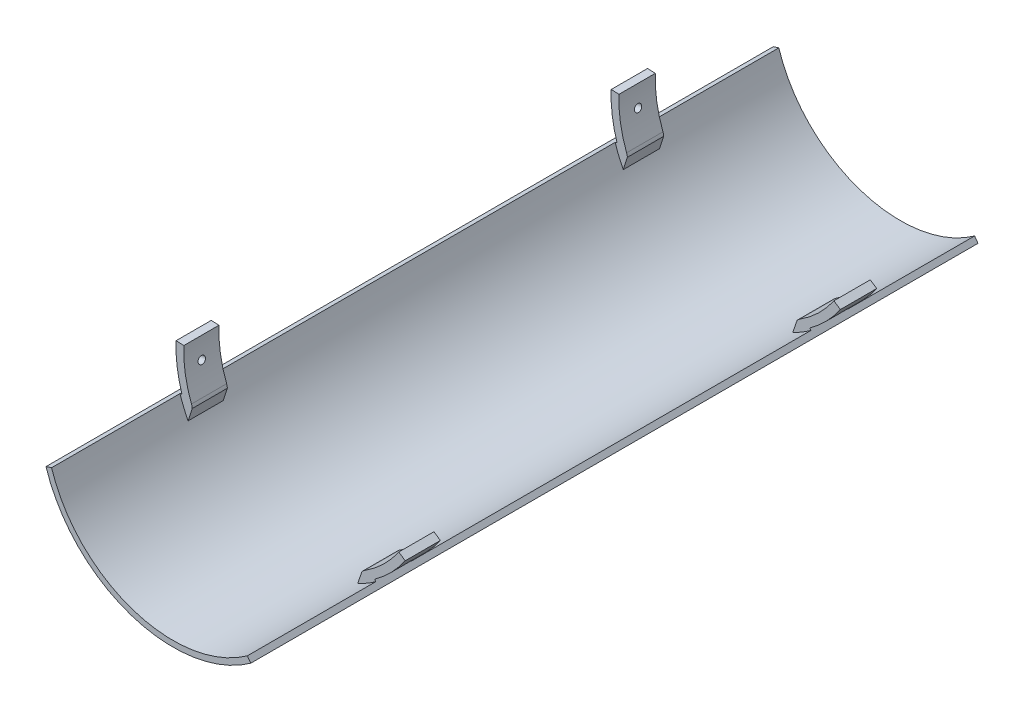
SolidWorks part; units mm, degrees
ref_plane "前视基准面" through (0, 0, 0) normal (0, 0, 1) x (1, 0, 0)
ref_plane "上视基准面" through (0, 0, 0) normal (0, 1, 0) x (1, 0, 0)
ref_plane "右视基准面" through (0, 0, 0) normal (1, 0, 0) x (0, 0, -1)
other "Configuration Table"
sketch "草图1" plane through (0, 0, 0) normal (0, 0, 1) x (1, 0, 0)
  line L0 (0, 0) -> (-52.4132, -16.6691) construction
  line L1 (0, 0) -> (32.0498, -44.6969) construction
  line L2 (-52.4132, -16.6691) -> (-49.3637, -15.6993)
  line L3 (30.1851, -42.0963) -> (32.0498, -44.6969)
  arc A0 (-49.3637, -15.6993) -> (30.1851, -42.0963) centre (0, 0) ccw
  arc A1 (-52.4132, -16.6691) -> (32.0498, -44.6969) centre (0, 0) ccw
  dimension "D1" = 110
  dimension "D2" = 103.6
  dimension "D3" = 108
extrude "凸台-拉伸1" add sketch "草图1" along normal mid plane 300
sketch "草图2" plane through (0, 0, -150) normal (0, 0, -1) x (-1, 0, 0)
  line L0 (0, 0) -> (-30.1851, -42.0963) construction
  line L1 (0, 0) -> (17.3221, -52.201) construction
  line L2 (-24.924, -42.0029) -> (-23.5075, -46.1588)
  line L3 (-40.1208, -27.4277) -> (-42.7625, -29.2337)
  line L4 (48.5589, 1.9992) -> (51.7562, 2.1309)
  line L5 (45.0905, -18.7697) -> (46.4395, -22.948)
  line L6 (0, 0) -> (-34.7485, -33.978) construction
  arc A1 (-40.1208, -27.4277) -> (-26.0428, -41.0333) centre (0, 0) ccw
  arc A2 (-32.0498, -44.6969) -> (52.4132, -16.6691) centre (0, 0) ccw construction
  arc A3 (-24.924, -42.0029) -> (-26.0428, -41.0333) centre (-28.7221, -45.2549) ccw
  arc A4 (-42.7625, -29.2337) -> (-23.5075, -46.1588) centre (0, 0) ccw
  arc A5 (51.7562, 2.1309) -> (46.4395, -22.948) centre (0, 0) cw
  arc A6 (45.0905, -18.7697) -> (45.4076, -17.3236) centre (50.0792, -19.1059) cw
  arc A7 (48.5589, 1.9992) -> (45.4076, -17.3236) centre (0, 0) cw
  dimension "D1" = 97.2
  dimension "D4" = 5
  dimension "D5" = 10
  dimension "D6" = 51.8
  dimension "D2" = 54
  dimension "D3" = 20
extrude "凸台-拉伸2" add sketch "草图2" against normal blind 247.5
sketch "草图3" plane through (0, 0, -150) normal (0, 0, -1) x (-1, 0, 0)
  circle A0 centre (0, 0) radius 52.6
extrude "切除-拉伸1" cut sketch "草图3" against normal blind 52.5
sketch "草图4" plane through (0, 0, 0) normal (0, 0, 1) x (1, 0, 0)
  circle A0 centre (0, 0) radius 52.6
extrude "切除-拉伸2" cut sketch "草图4" along normal mid plane 165
sketch "草图5" plane through (0, 0, -150) normal (0, 0, -1) x (-1, 0, 0)
  line L0 (0, 0) -> (-32.0498, -44.6969)
  line L1 (0, 0) -> (-37.0365, -36.2152)
  line L2 (0, 0) -> (30.9591, -31.6612)
  line L3 (0, 0) -> (52.4132, -16.6691)
  line L4 (0, 0) -> (55.6923, -7.4729)
  line L5 (0, 0) -> (-5.7306, -42.7077)
  arc A0 (-42.7625, -29.2337) -> (-30.1851, -42.0963) centre (0, 0) ccw construction
  dimension "D1" = 10
  dimension "D2" = 10
ref_plane "基准面1" through (0, 0, 0) normal (0.715, -0.6991, 0) x (-0.6991, -0.715, 0)
sketch "草图6" plane through (0, 0, 0) normal (0.715, -0.6991, 0) x (-0.6991, -0.715, 0)
  line L0 (0, 150) -> (0, -164.5168) construction
  circle A0 centre (0, 90) radius 1.5
  circle A1 centre (0, -90) radius 1.5
  dimension "D1" = 3
  dimension "D2" = 3
  dimension "D3" = 60
  dimension "D4" = 240
extrude "切除-拉伸3" cut sketch "草图6" along normal blind 165
ref_plane "基准面3" through (0, 0, 0) normal (0.9911, 0.133, 0) x (0.133, -0.9911, 0)
sketch "草图7" plane through (0, 0, 0) normal (0.9911, 0.133, 0) x (0.133, -0.9911, 0)
  line L0 (0, 150) -> (0, -135.6873) construction
  circle A0 centre (0, 90) radius 1.5
  circle A1 centre (0, -90) radius 1.5
  dimension "D3" = 3
  dimension "D4" = 3
  dimension "D1" = 60
  dimension "D2" = 240
extrude "切除-拉伸4" cut sketch "草图7" against normal blind 165
sketch "草图8" plane through (0, 0, -150) normal (0, 0, -1) x (-1, 0, 0)
  line L0 (-24.924, -42.0029) -> (-23.1321, -47.2405)
  line L1 (45.0905, -18.7697) -> (46.7894, -24.0315)
  line L2 (-24.924, -42.0029) -> (45.0905, -18.7697)
  arc A0 (-23.1321, -47.2405) -> (46.7894, -24.0315) centre (0, 0) ccw
  dimension "D1" = 52.6
extrude "切除-拉伸5" cut sketch "草图8" against normal blind 500
sketch "草图9" plane through (0, 0, 150) normal (0, 0, 1) x (1, 0, 0)
  circle A0 centre (0, 0) radius 52.6
extrude "切除-拉伸6" cut sketch "草图9" against normal blind 53
